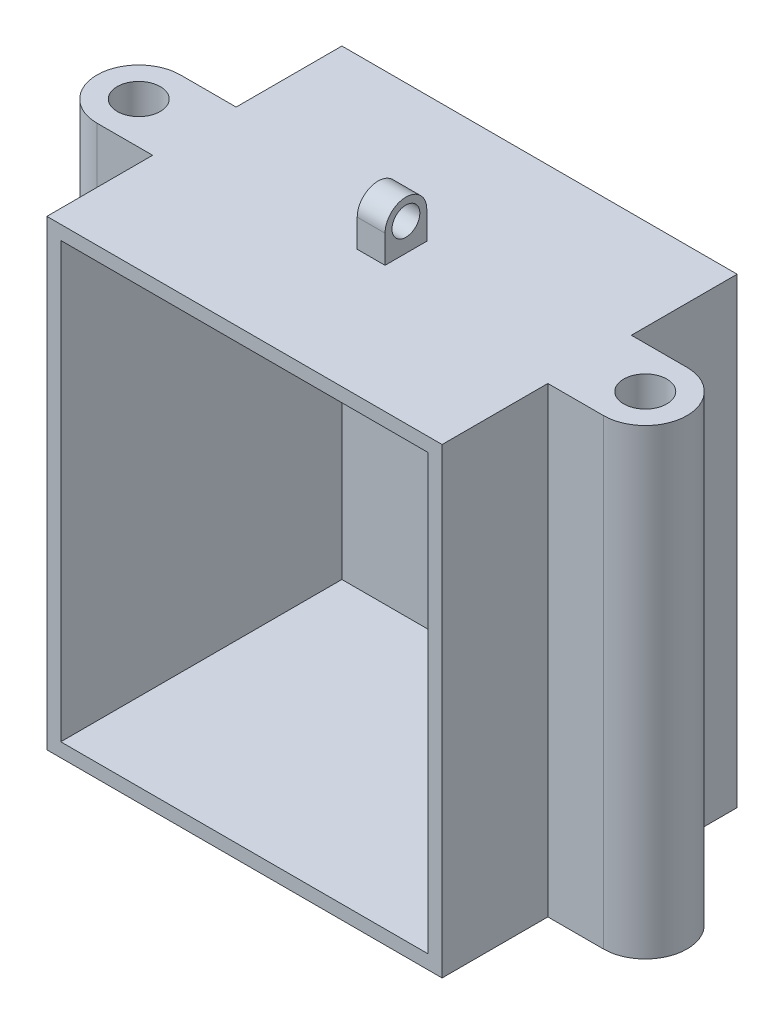
SolidWorks part; units mm, degrees
ref_plane "정면" through (0, 0, 0) normal (0, 0, 1) x (1, 0, 0)
ref_plane "윗면" through (0, 0, 0) normal (0, 1, 0) x (1, 0, 0)
ref_plane "우측면" through (0, 0, 0) normal (1, 0, 0) x (0, 0, -1)
sketch "스케치2" plane through (0, 0, 0) normal (0, 0, 1) x (1, 0, 0)
  line L1 (0, 0) -> (142, 0)
  line L2 (0, 0) -> (0, 166)
  line L3 (0, 166) -> (142, 166)
  line L4 (142, 0) -> (142, 166)
  dimension "D1" = 166
  dimension "D2" = 142
extrude "보스-돌출1" add sketch "스케치2" along normal blind 106
shell "쉘1" thickness 5
sketch "스케치3" plane through (0, 166, 0) normal (0, 1, 0) x (1, 0, 0)
  line L0 (-20, -38) -> (0, -38)
  line L1 (0, -106) -> (0, 0) construction
  line L2 (-20, -68) -> (0, -68)
  line L3 (162, -38) -> (142, -38)
  line L4 (142, -106) -> (142, 0) construction
  line L5 (162, -68) -> (142, -68)
  circle A0 centre (-20, -53) radius 7.75
  circle A1 centre (162, -53) radius 7.75
  circle A2 centre (-20, -53) radius 15
  circle A3 centre (162, -53) radius 15
  point P18 (0, 0)
  point P19 (142, -53)
  point P20 (0, 0)
  point P21 (0, -53)
  line M5 (0, 0) -> (0, -106)
  line M7 (142, -106) -> (142, 0)
  dimension "D1" = 15.5
  dimension "D2" = 30
  dimension "D3" = 30
  dimension "D4" = 20
  dimension "D5" = 20
extrude "보스-돌출2" add sketch "스케치3" against normal blind 166 contours A2 A0 | A2 L2 L0 M5 | A3 L3 L5 M7 | A3 A1
ref_plane "평면1" through (71, 0, 0) normal (1, 0, 0) x (0, 0, -1)
sketch "스케치4" plane through (71, 0, 0) normal (1, 0, 0) x (0, 0, -1)
  line L0 (-45.5, 176) -> (-45.5, 166)
  line L1 (-38, 166) -> (-68, 166) construction
  line L2 (-60.5, 176) -> (-60.5, 166)
  line L3 (-45.5, 166) -> (-60.5, 166)
  circle A0 centre (-53, 176) radius 7.5
  circle A1 centre (-53, 176) radius 5
  point P9 (-53, 166)
  dimension "D1" = 15
  dimension "D3" = 10
  dimension "D2" = 10
extrude "보스-돌출3" add sketch "스케치4" along normal mid plane 10 contours A0 L2 L3 L0 | A1
